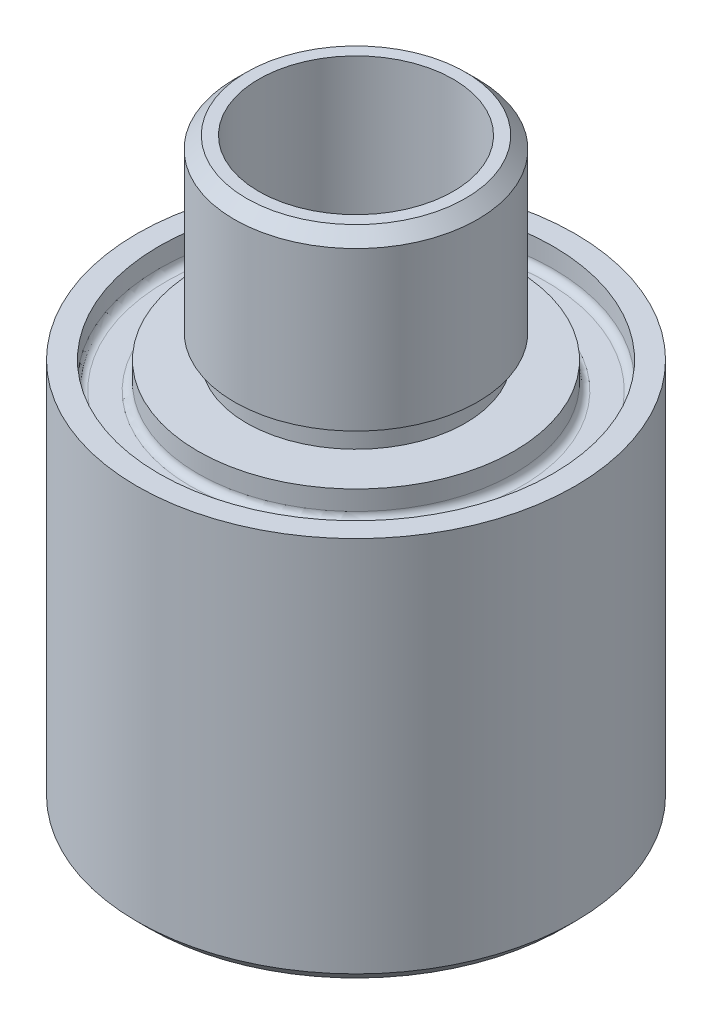
SolidWorks part; units mm, degrees
ref_plane "前视基准面" through (0, 0, 0) normal (0, 0, 1) x (1, 0, 0)
ref_plane "上视基准面" through (0, 0, 0) normal (0, 1, 0) x (1, 0, 0)
ref_plane "右视基准面" through (0, 0, 0) normal (1, 0, 0) x (0, 0, -1)
other "Configuration Table"
sketch "草图1" plane through (0, 0, 0) normal (0, 1, 0) x (1, 0, 0)
  circle A0 centre (0, 0) radius 9
  dimension "D1" = 18
extrude "凸台-拉伸1" add sketch "草图1" along normal blind 16
sketch "草图2" plane through (0, 0, 0) normal (0, -1, 0) x (1, 0, 0)
  circle A0 centre (0, 0) radius 7.5
  dimension "D1" = 15
extrude "切除-拉伸1" cut sketch "草图2" against normal blind 12.5
sketch "草图4" plane through (0, 16, 0) normal (0, 1, 0) x (1, 0, 0)
  circle A0 centre (0, 0) radius 4.5
  dimension "D1" = 9
extrude "凸台-拉伸2" add sketch "草图4" along normal blind 1
sketch "草图5" plane through (0, 17, 0) normal (0, 1, 0) x (1, 0, 0)
  circle A0 centre (0, 0) radius 5
  dimension "D1" = 10
extrude "凸台-拉伸3" add sketch "草图5" along normal blind 7
sketch "草图6" plane through (0, 16, 0) normal (0, 1, 0) x (1, 0, 0)
  circle A0 centre (0, 0) radius 8.1
  circle A1 centre (0, 0) radius 6.5
  dimension "D1" = 16.2
  dimension "D2" = 13
extrude "切除-拉伸2" cut sketch "草图6" against normal blind 1.1
chamfer "倒角1" distance 0.5 angle 45 1 edges at (0, 24, 5)
fillet "圆角1" radius 0.3 2 edges at (0, 14.9, 6.5) (0, 14.9, 8.1)
sketch "草图15" plane through (0, 24, 0) normal (0, 1, 0) x (1, 0, 0)
  circle A0 centre (0, 0) radius 4
  dimension "D1" = 8
extrude "切除-拉伸4" cut sketch "草图15" against normal blind 11.5
chamfer "倒角4" distance 0.5 angle 45 1 edges at (0, 12.5, 4)
chamfer "倒角5" distance 0.5 angle 45 1 edges at (0, 0, 9)
